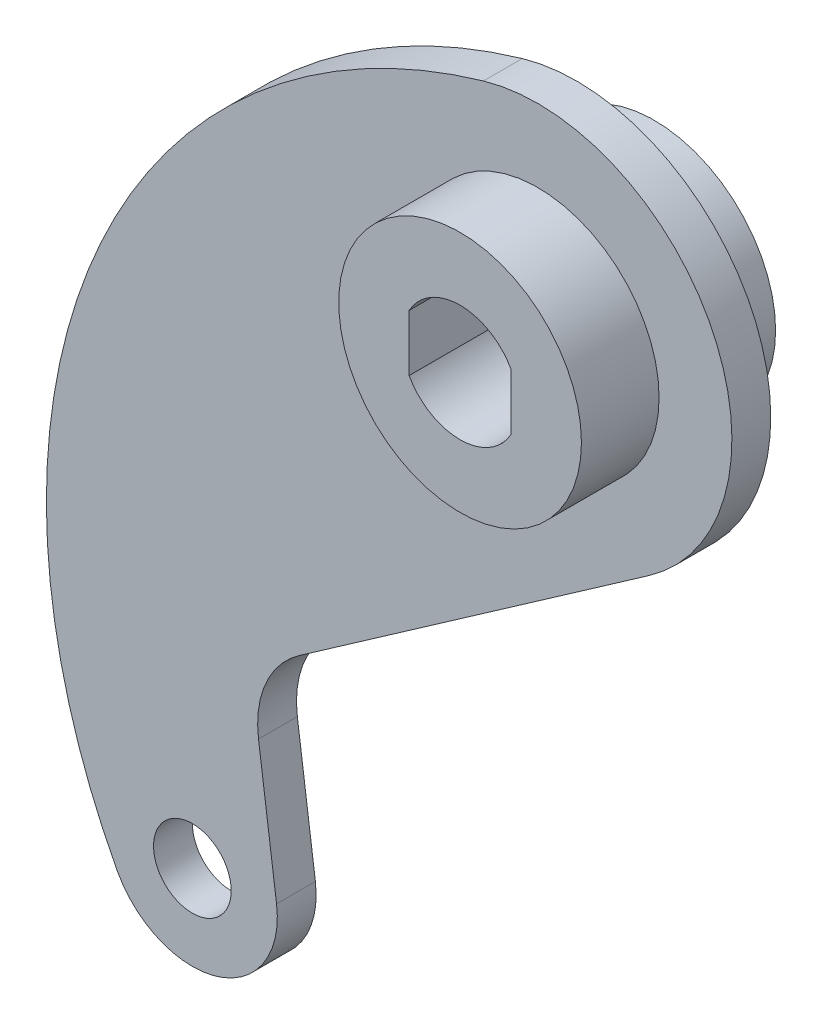
SolidWorks part; units mm, degrees
ref_plane "Front Plane" through (0, 0, 0) normal (0, 0, 1) x (1, 0, 0)
ref_plane "Top Plane" through (0, 0, 0) normal (0, 1, 0) x (1, 0, 0)
ref_plane "Right Plane" through (0, 0, 0) normal (1, 0, 0) x (0, 0, -1)
sketch "Sketch1" plane through (0, 0, 0) normal (0, 0, 1) x (1, 0, 0)
  line L0 (0, 0) -> (0, -15) construction
  line L4 (-4, -11.3137) -> (-4, -15) construction
  line L5 (-4, -15) -> (4, -15) construction
  line L6 (4, -11.3137) -> (4, -15) construction
  line L7 (-5.2184, -2.0512) -> (4, -15) construction
  line L8 (-4, -15) -> (4.9923, -2.3686) construction
  arc A0 (0, -12) -> (-1.7708, -11.8686) centre (0, 0) ccw construction
  circle A1 centre (0, 0) radius 25
  circle A2 centre (0, 0) radius 15 construction
  circle A3 centre (0, 0) radius 12
  point P7 (0, -9.3813)
  dimension "D1" = 24
  dimension "D2" = 50
  dimension "D5" = 3
  dimension "D4" = 8
extrude "Boss-Extrude1" add sketch "Sketch1" along normal blind 40
sketch "Sketch3" plane through (0, 0, 40) normal (0, 0, 1) x (1, 0, 0)
  line L0 (-53.8054, -129.7126) -> (-59.1544, -90.0718)
  line L1 (-59.1544, -90.0718) -> (22.8949, -32.7997)
  line L4 (-71.1483, -132.0527) -> (0, 0) construction
  line L5 (0, 0) -> (0, -187.155) construction
  arc A0 (22.8949, -32.7997) -> (-11.1906, 38.4028) centre (0, 0) ccw
  circle A1 centre (0, 0) radius 25
  arc A2 (22.8949, -32.7997) -> (-11.1906, 38.4028) centre (0, 0) ccw
  circle A3 centre (-71.1483, -132.0527) radius 8
  arc A4 (-86.6017, -140.265) -> (-53.8054, -129.7126) centre (-71.1483, -132.0527) ccw
  arc A6 (-11.1906, 38.4028) -> (-86.6017, -140.265) centre (23.7799, -81.6058) ccw
  circle A7 centre (0, 0) radius 12 construction
  dimension "D2" = 50
  dimension "D3" = 40
  dimension "D5" = 16
  dimension "D6" = 17.5
  dimension "D7" = 125
  dimension "D1" = 28.315
  dimension "D4" = 150
  dimension "D8" = 40
  dimension "D9" = 36
extrude "Boss-Extrude2" add sketch "Sketch3" against normal blind 8 separate body
fillet "Fillet1" radius 20 1 edges at (-59.1544, -90.0718, 36)
move or copy body "Body-Move/Copy1" bodies to move or copy 103 copy no translate (0, 0, -16)
sketch "Sketch4" plane through (0, 0, 40) normal (0, 0, 1) x (1, 0, 0)
  line L0 (0, 0) -> (0, 23.6207) construction
  line L1 (-10.5, 0) -> (10.5, 0) construction
  line L2 (-10.5, -5.8095) -> (-10.5, 5.8095)
  line L3 (10.5, -5.8095) -> (10.5, 5.8095)
  arc A1 (10.5, -5.8095) -> (10.5, 5.8095) centre (0, 0) ccw
  arc A2 (-10.5, 5.8095) -> (-10.5, -5.8095) centre (0, 0) ccw
  circle A3 centre (0, 0) radius 12 construction
  point P5 (0, 0)
  point P12 (-10.5, 0)
  dimension "D1" = 21
extrude "Boss-Extrude3" add sketch "Sketch4" against normal up to surface (40 mm away) up to face at (25, 0, 0)
